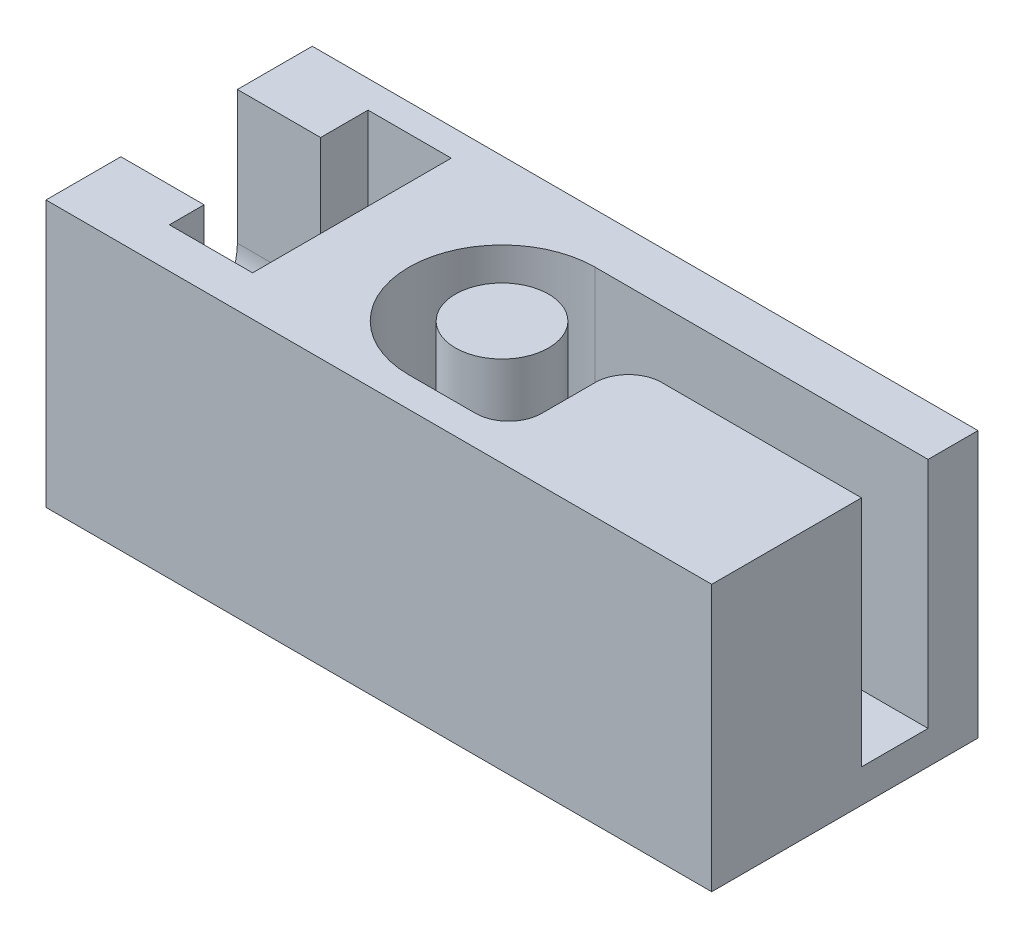
SolidWorks part; units mm, degrees
ref_plane "Front Plane" through (0, 0, 0) normal (0, 0, 1) x (1, 0, 0)
ref_plane "Top Plane" through (0, 0, 0) normal (0, 1, 0) x (1, 0, 0)
ref_plane "Right Plane" through (0, 0, 0) normal (1, 0, 0) x (0, 0, -1)
sketch "Sketch1" plane through (0, 0, 0) normal (0, 1, 0) x (1, 0, 0)
  line L1 (0, 0) -> (20, 0)
  line L2 (0, 0) -> (0, 8)
  line L3 (0, 8) -> (20, 8)
  line L4 (20, 0) -> (20, 8)
  dimension "D1" = 8
  dimension "D2" = 20
extrude "Boss-Extrude1" add sketch "Sketch1" along normal blind 8
sketch "Sketch2" plane through (0, 8, 0) normal (0, 1, 0) x (1, 0, 0)
  line L0 (20, 6.5) -> (10, 6.5)
  line L1 (20, 0) -> (20, 8) construction
  line L2 (10, 0.9) -> (12, 0.9)
  line L3 (13, 1.9) -> (13, 3.5)
  line L4 (14, 4.5) -> (20, 4.5)
  line L5 (20, 4.5) -> (20, 6.5)
  line L6 (0, 0) -> (20, 0) construction
  arc A0 (10, 6.5) -> (10, 0.9) centre (10, 3.7) ccw
  circle A1 centre (10, 3.7) radius 1.4
  arc A2 (13, 3.5) -> (14, 4.5) centre (14, 3.5) cw
  arc A3 (12, 0.9) -> (13, 1.9) centre (12, 1.9) ccw
  point P16 (13, 0.9)
  point P17 (10, 0.4)
  dimension "D4" = 2.8
  dimension "D6" = 1.4
  dimension "D7" = 1
  dimension "D1" = 6.5
  dimension "D2" = 10
  dimension "D3" = 2
  dimension "D5" = 3
extrude "Cut-Extrude1" cut sketch "Sketch2" against normal blind 7
sketch "Sketch4" plane through (0, 0, 0) normal (-1, 0, 0) x (0, 0, 1)
  line L0 (-8, 0) -> (0, 8) construction
  line L1 (-5.75, 4) -> (-5.75, 8)
  line L2 (-8, 8) -> (0, 8) construction
  line L3 (-5.75, 8) -> (-2.25, 8)
  line L4 (-2.25, 8) -> (-2.25, 4)
  arc A0 (-5.75, 4) -> (-2.25, 4) centre (-4, 4) ccw
  dimension "D1" = 3.5
extrude "Cut-Extrude2" cut sketch "Sketch4" against normal blind 5
sketch "Sketch5" plane through (5, 0, 0) normal (-1, 0, 0) x (0, 0, 1)
  line L0 (-7.1754, 3.5) -> (-7.1754, 14.0662)
  line L1 (-7.1754, 3.5) -> (-5.079, 1.0135)
  line L2 (-5.079, 1.0135) -> (-1.9532, 1.5723)
  line L3 (-1.9532, 1.5723) -> (-1.2068, 3.6381)
  line L7 (-1.2068, 3.6381) -> (-1.2068, 14.0662)
  line L8 (-1.2068, 14.0662) -> (-7.1754, 14.0662)
  line L9 (-6.0468, 6.4277) -> (-6.5864, 4.9345) [skipped]
  line L10 (-2.921, 6.9865) -> (-4.4839, 6.7071) [skipped]
  line L11 (-0.8741, 4.5588) -> (-1.8975, 5.7726) [skipped]
  circle A0 centre (-4, 4) radius 2.75 construction
  dimension "D1" = 5.5
extrude "Cut-Extrude3" cut sketch "Sketch5" along normal blind 2.5
